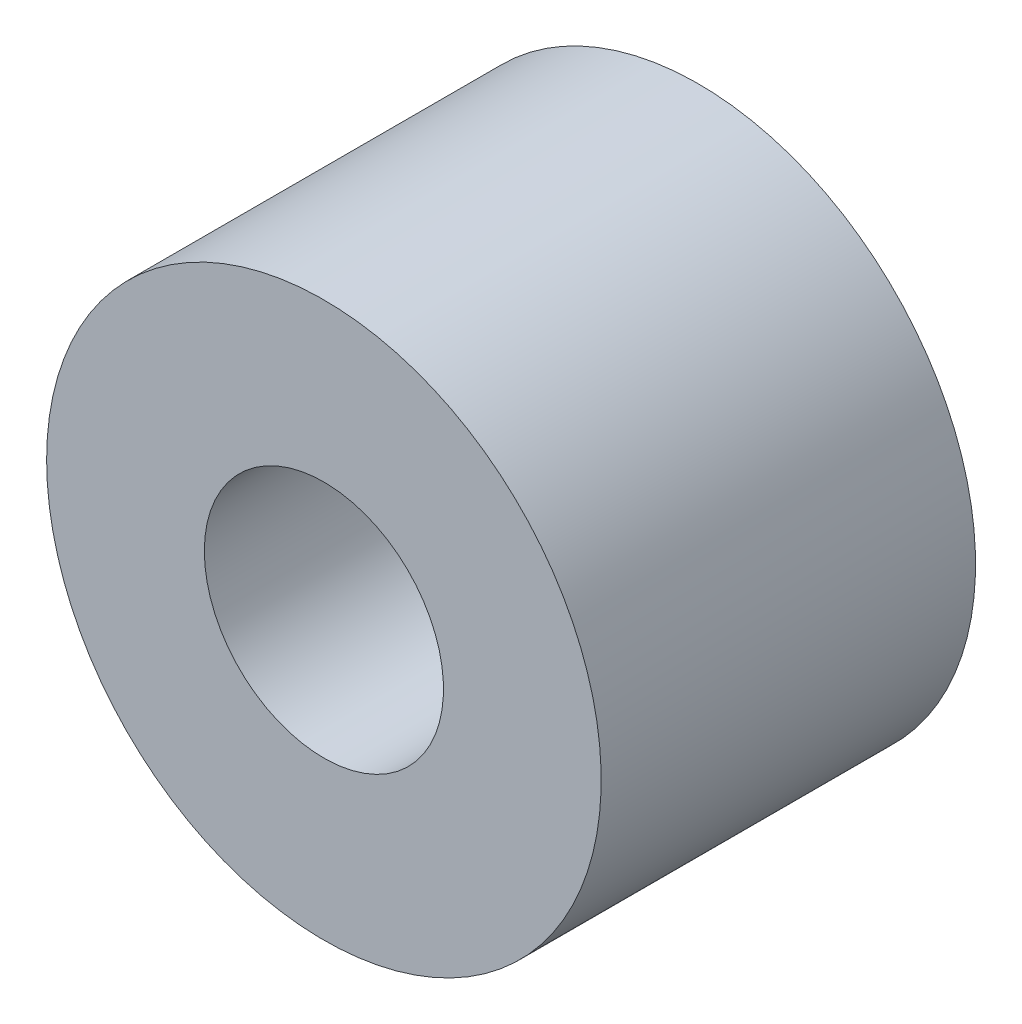
SolidWorks part; units mm, degrees
ref_plane "Alzado" through (0, 0, 0) normal (0, 0, 1) x (1, 0, 0)
ref_plane "Planta" through (0, 0, 0) normal (0, 1, 0) x (1, 0, 0)
ref_plane "Vista lateral" through (0, 0, 0) normal (1, 0, 0) x (0, 0, -1)
sketch "Sketch1" plane through (0, 0, 0) normal (0, 0, 1) x (1, 0, 0)
  circle A0 centre (0, 0) radius 1.725
  circle A1 centre (0, 0) radius 4
  dimension "D1" = 3.45
  dimension "D2" = 8
extrude "Boss-Extrude1" add sketch "Sketch1" along normal blind 5.4
